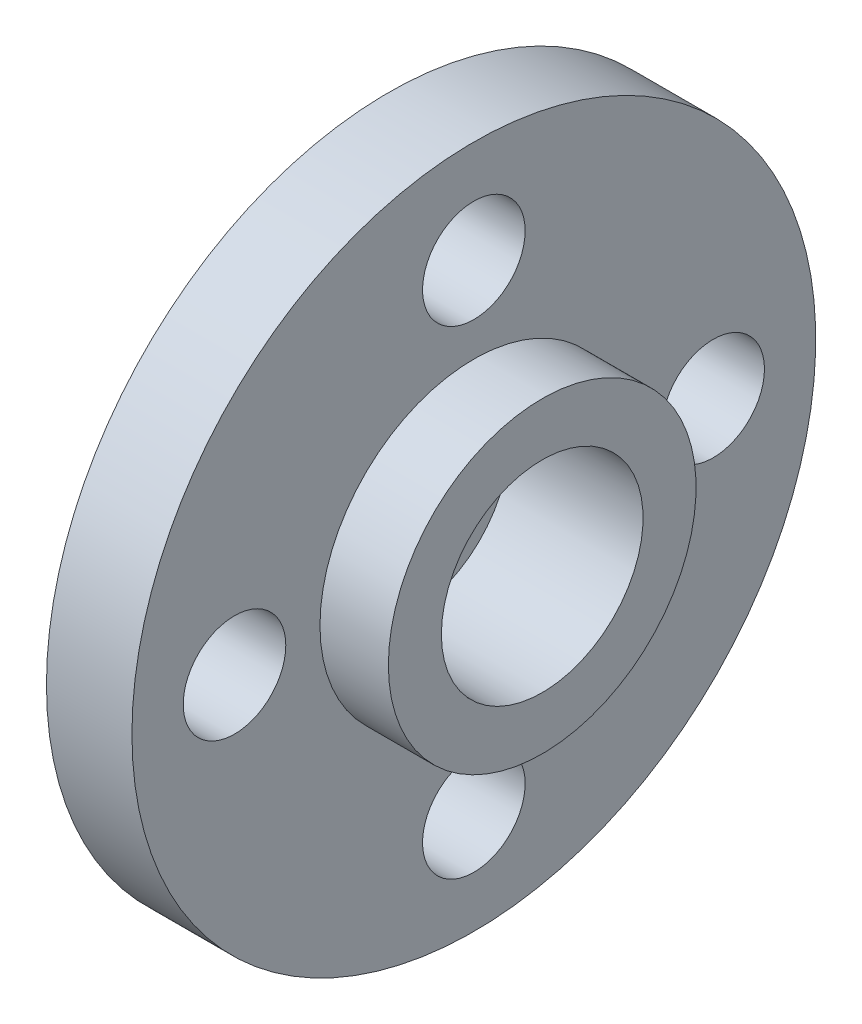
SolidWorks part; units mm, degrees
ref_plane "前视基准面" through (0, 0, 0) normal (0, 0, 1) x (1, 0, 0)
ref_plane "上视基准面" through (0, 0, 0) normal (0, 1, 0) x (1, 0, 0)
ref_plane "右视基准面" through (0, 0, 0) normal (1, 0, 0) x (0, 0, -1)
sketch "草图1" plane through (0, 0, 0) normal (0, 0, 1) x (1, 0, 0)
  line L0 (-8.5884, 0) -> (8.4297, 0) construction
  line L1 (-2.5794, 1.5) -> (-2.5794, 10)
  line L2 (-2.5794, 10) -> (-0.0794, 10)
  line L3 (-0.0794, 10) -> (-0.0794, 4.5)
  line L4 (-0.0794, 4.5) -> (1.9206, 4.5)
  line L5 (1.9206, 4.5) -> (1.9206, 2.95)
  line L6 (1.9206, 2.95) -> (-1.9898, 2.95)
  line L7 (-1.9898, 2.95) -> (-1.9898, 1.5)
  line L8 (-1.9898, 1.5) -> (-2.5794, 1.5)
  dimension "D1" = 2.5
  dimension "D2" = 2
  dimension "D3" = 1.5
  dimension "D4" = 10
  dimension "D5" = 4.5
  dimension "D6" = 2.95
revolve "旋转1" add sketch "草图1" angle 360 about L0
sketch "草图2" plane through (-0.0794, 0, 0) normal (1, 0, 0) x (0, 0, -1)
  circle A0 centre (0, 7) radius 1.5
  circle A1 centre (7, 0) radius 1.5
  circle A2 centre (0, -7) radius 1.5
  circle A3 centre (-7, 0) radius 1.5
  point P12 (0, 0)
  dimension "D2" = 3
  dimension "D1" = 7
  dimension "D3" = 4
extrude "切除-拉伸1" cut sketch "草图2" against normal blind 10
